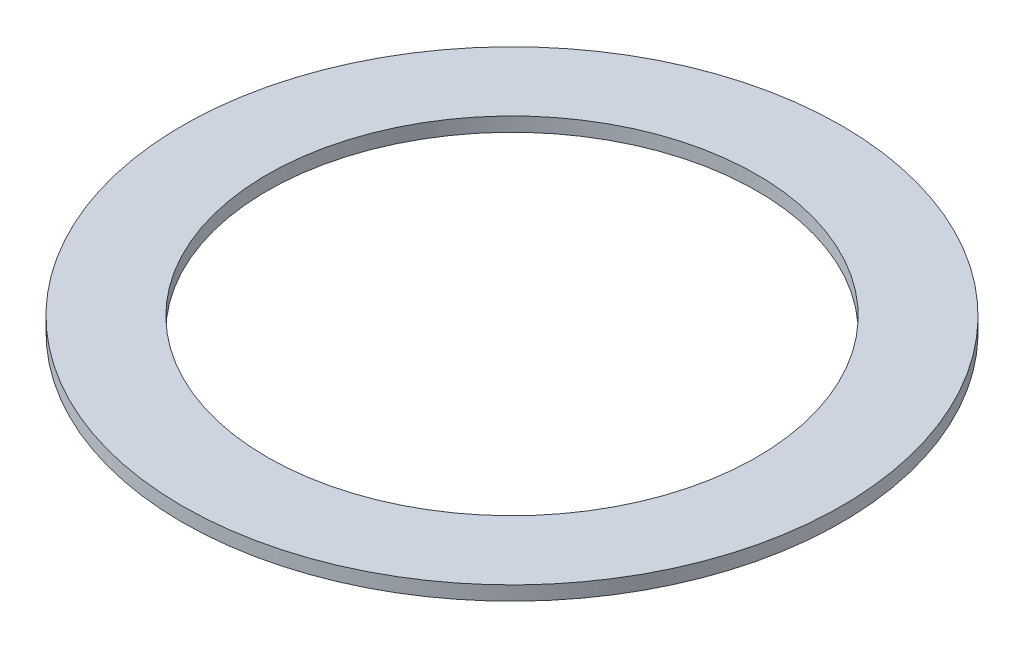
SolidWorks part; units mm, degrees
ref_plane "Front Plane" through (0, 0, 0) normal (0, 0, 1) x (1, 0, 0)
ref_plane "Top Plane" through (0, 0, 0) normal (0, 1, 0) x (1, 0, 0)
ref_plane "Right Plane" through (0, 0, 0) normal (1, 0, 0) x (0, 0, -1)
sketch "Sketch1" plane through (0, 0, 0) normal (0, 1, 0) x (1, 0, 0)
  circle A0 centre (0, 0) radius 13
  circle A1 centre (0, 0) radius 17.5
  dimension "D1" = 26
  dimension "D2" = 35
extrude "Boss-Extrude1" add sketch "Sketch1" along normal blind 0.75
